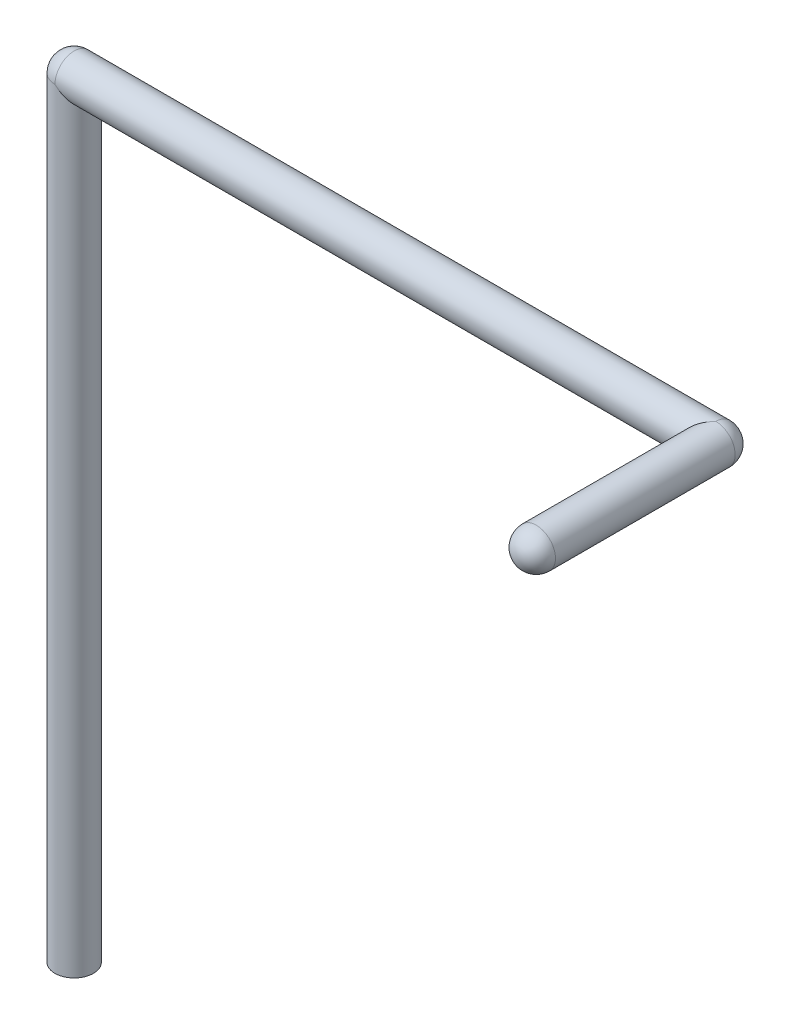
SolidWorks part; units mm, degrees
ref_plane "前视基准面" through (0, 0, 0) normal (0, 0, 1) x (1, 0, 0)
ref_plane "上视基准面" through (0, 0, 0) normal (0, 1, 0) x (1, 0, 0)
ref_plane "右视基准面" through (0, 0, 0) normal (1, 0, 0) x (0, 0, -1)
other "Configuration Table"
sketch "草图1" plane through (0, 0, 0) normal (0, 1, 0) x (1, 0, 0)
  circle A0 centre (0, 0) radius 0.75
  dimension "D1" = 1.5
extrude "凸台-拉伸1" add sketch "草图1" along normal blind 30
sketch "草图2" plane through (0, 0, 0) normal (1, 0, 0) x (0, 0, -1)
  line L0 (0.75, 30) -> (-0.75, 30) construction
  line L1 (0, 30.75) -> (0, 29.25)
  arc A0 (0, 29.25) -> (0, 30.75) centre (0, 30) ccw
revolve "旋转1" add sketch "草图2" angle 360 about L1
sketch "草图3" plane through (0, 0, 0) normal (1, 0, 0) x (0, 0, -1)
  line L0 (-0.75, 30) -> (0.75, 30) construction
  circle A0 centre (0, 30) radius 0.75
  dimension "D1" = 1.5
extrude "凸台-拉伸2" add sketch "草图3" along normal blind 25
sketch "草图4" plane through (0, 0, 0) normal (0, 0, 1) x (1, 0, 0)
  line L0 (25, 29.25) -> (25, 30.75) construction
  line L1 (24.25, 30) -> (25.75, 30)
  arc A0 (25.75, 30) -> (24.25, 30) centre (25, 30) ccw
revolve "旋转2" add sketch "草图4" angle 360 about L1
sketch "草图5" plane through (0, 0, 0) normal (0, 0, 1) x (1, 0, 0)
  line L0 (25, 30.75) -> (25, 29.25) construction
  circle A0 centre (25, 30) radius 0.75
  dimension "D1" = 1.5
extrude "凸台-拉伸3" add sketch "草图5" along normal blind 7
sketch "草图6" plane through (0, 0, 7) normal (0, 0, 1) x (1, 0, 0)
  line L0 (25, 30.75) -> (25, 29.25)
  arc A0 (25, 29.25) -> (25, 30.75) centre (25, 30) ccw
  circle A1 centre (25, 30) radius 0.75 construction
  dimension "D1" = 0.75
revolve "旋转3" add sketch "草图6" angle 360 about L0
